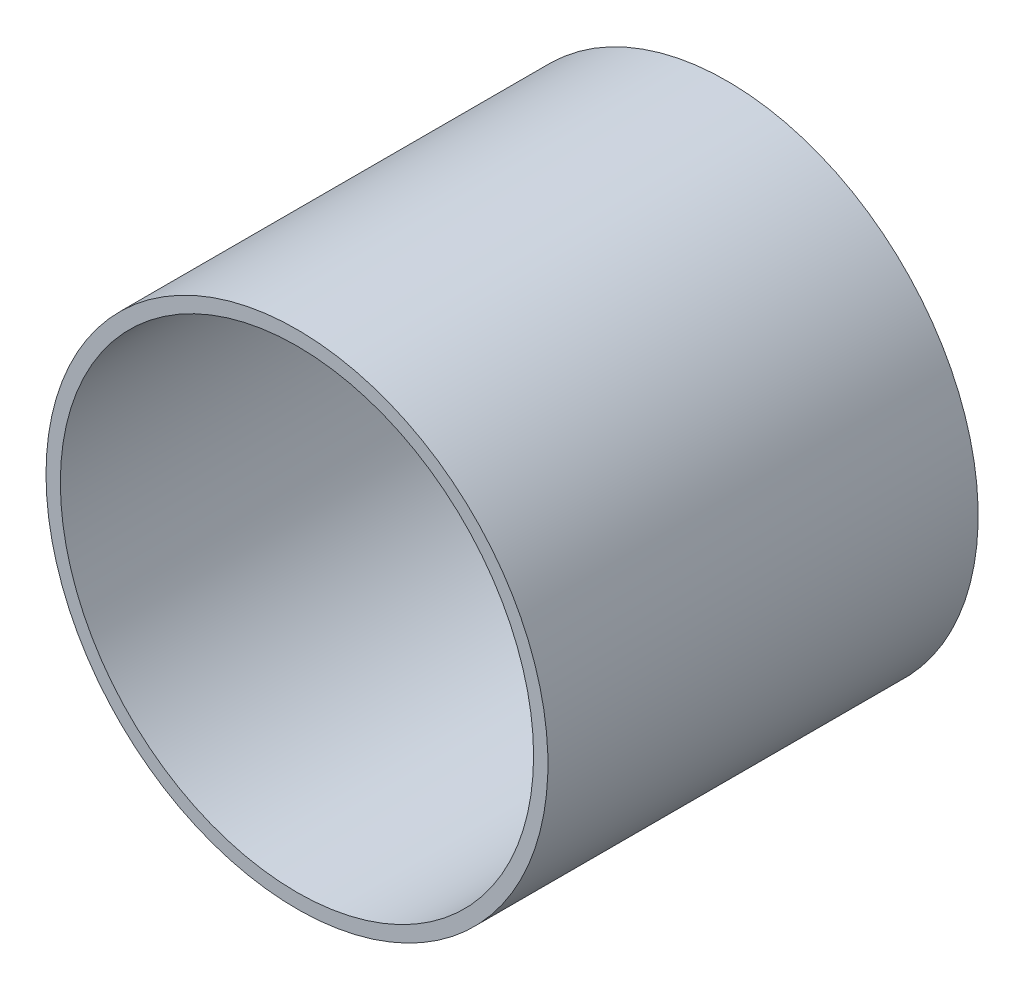
SolidWorks part; units mm, degrees
ref_plane "Front Plane" through (0, 0, 0) normal (0, 0, 1) x (1, 0, 0)
ref_plane "Top Plane" through (0, 0, 0) normal (0, 1, 0) x (1, 0, 0)
ref_plane "Right Plane" through (0, 0, 0) normal (1, 0, 0) x (0, 0, -1)
sketch "Sketch2" plane through (0, 0, 0) normal (0, 0, 1) x (1, 0, 0)
  circle A0 centre (0, 0) radius 44.45
extrude "Boss-Extrude1" add sketch "Sketch2" along normal blind 76.2
shell "Shell1" thickness 2.54
sketch "Sketch3" plane through (0, 0, 73.66) normal (0, 0, -1) x (-1, 0, 0)
  circle A1 centre (0, 0) radius 41.91
  circle A2 centre (0, 0) radius 41.91
  dimension "D1" = 0
extrude "Cut-Extrude1" cut sketch "Sketch3" against normal blind 76.2
